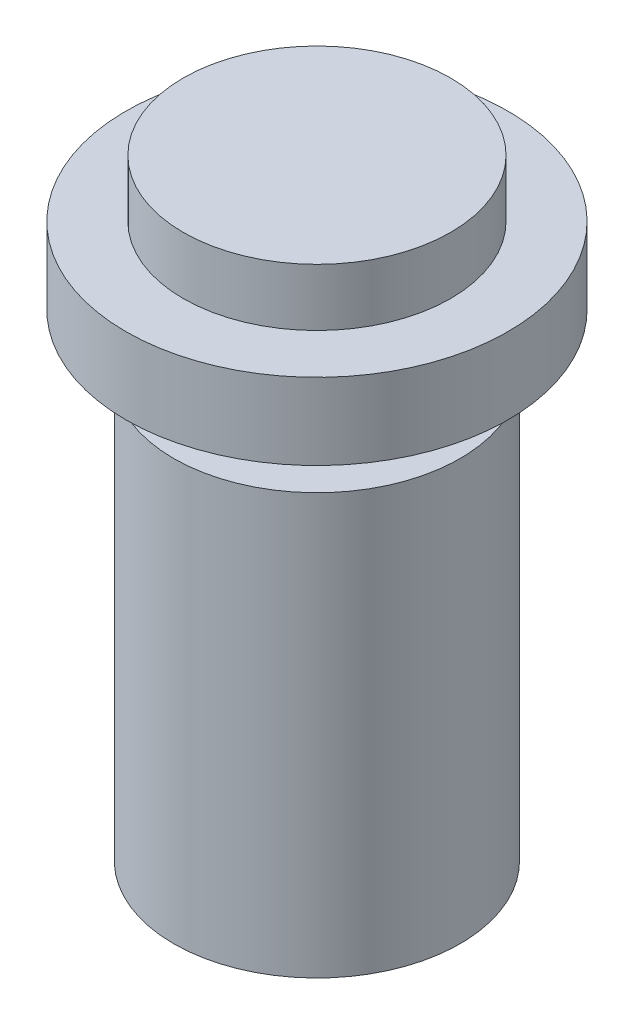
SolidWorks part; units mm, degrees
ref_plane "Front Plane" through (0, 0, 0) normal (0, 0, 1) x (1, 0, 0)
ref_plane "Top Plane" through (0, 0, 0) normal (0, 1, 0) x (1, 0, 0)
ref_plane "Right Plane" through (0, 0, 0) normal (1, 0, 0) x (0, 0, -1)
sketch "SK_P01_Bezel" plane through (0, 0, 0) normal (0, 1, 0) x (1, 0, 0)
  circle A0 centre (0, 0) radius 10
extrude "P01_Bezel" add sketch "SK_P01_Bezel" along normal blind 4 from offset 25
sketch "SK_P02_Lens" plane through (0, 0, 0) normal (0, 1, 0) x (1, 0, 0)
  circle A0 centre (0, 0) radius 7
extrude "P02_Lens" add sketch "SK_P02_Lens" along normal blind 3 from offset 29
sketch "SK_P03_Body" plane through (0, 0, 0) normal (0, 1, 0) x (1, 0, 0)
  circle A0 centre (0, 0) radius 7.5
extrude "P03_Body" add sketch "SK_P03_Body" along normal blind 22
